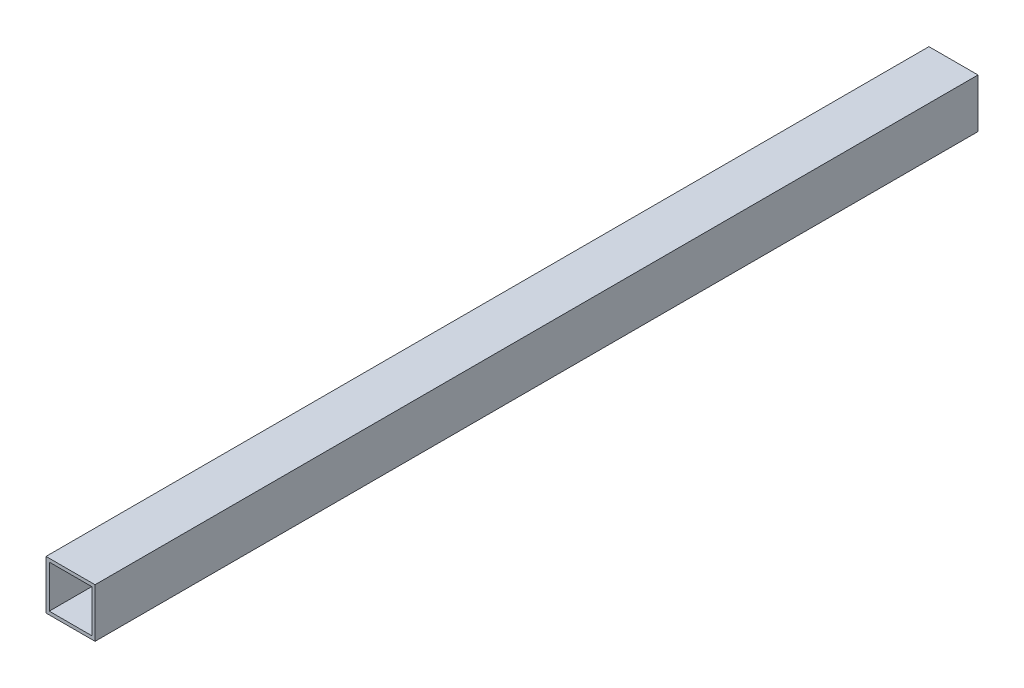
SolidWorks part; units mm, degrees
material "1060 Alloy"
ref_plane "Front Plane" through (0, 0, 0) normal (0, 0, 1) x (1, 0, 0)
ref_plane "Top Plane" through (0, 0, 0) normal (0, 1, 0) x (1, 0, 0)
ref_plane "Right Plane" through (0, 0, 0) normal (1, 0, 0) x (0, 0, -1)
sketch "Sketch1" plane through (0, 0, 0) normal (0, 0, 1) x (1, 0, 0)
  line L0 (-7.5, 7.5) -> (7.5, 7.5)
  line L1 (-6.5, 6.5) -> (6.5, 6.5)
  line L2 (-6.5, 6.5) -> (-6.5, -6.5)
  line L3 (-6.5, -6.5) -> (6.5, -6.5)
  line L4 (6.5, 6.5) -> (6.5, -6.5)
  line L5 (-6.5, 6.5) -> (6.5, -6.5) construction
  line L6 (-6.5, -6.5) -> (6.5, 6.5) construction
  line L7 (7.5, 7.5) -> (7.5, -7.5)
  line L8 (-7.5, -7.5) -> (7.5, -7.5)
  line L9 (-7.5, 7.5) -> (-7.5, -7.5)
  point P0 (0, 0)
  dimension "D2" = 15
  dimension "D3" = 15
  dimension "D1" = 1
extrude "Boss-Extrude1" add sketch "Sketch1" along normal blind 270
